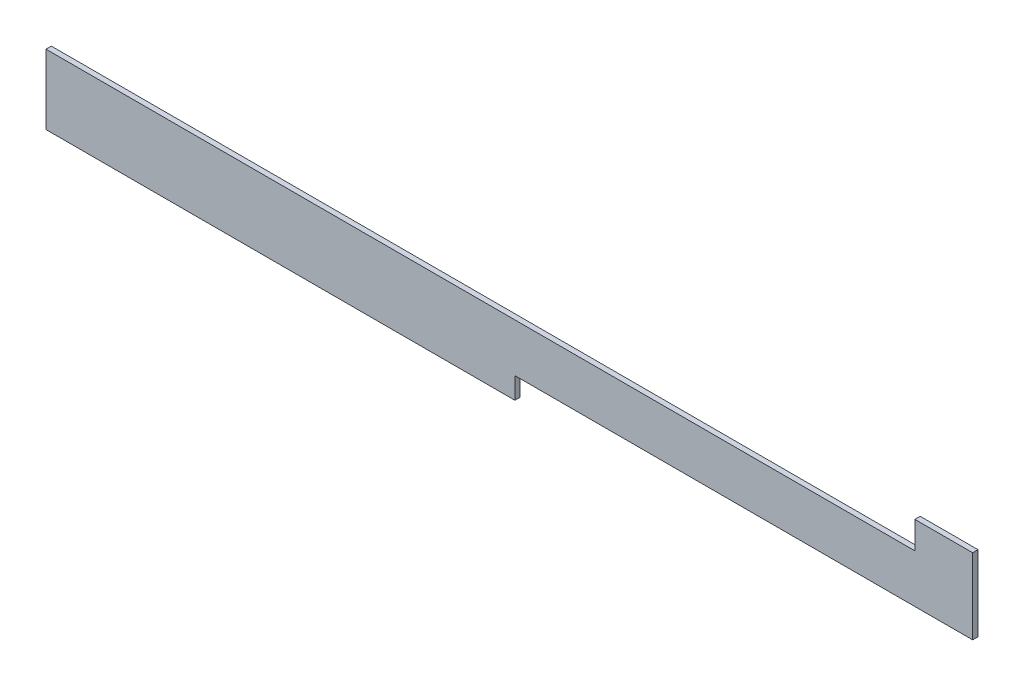
SolidWorks part; units mm, degrees
ref_plane "Front Plane" through (0, 0, 0) normal (0, 0, 1) x (1, 0, 0)
ref_plane "Top Plane" through (0, 0, 0) normal (0, 1, 0) x (1, 0, 0)
ref_plane "Right Plane" through (0, 0, 0) normal (1, 0, 0) x (0, 0, -1)
sketch "Sketch1" plane through (0, 0, 0) normal (0, 0, 1) x (1, 0, 0)
  line L0 (241.1095, 30.5435) -> (241.1095, 14.351)
  line L1 (275.5036, -14.351) -> (3.302, -14.351)
  line L2 (275.5036, -14.351) -> (275.5036, 14.351)
  line L3 (241.1095, 14.351) -> (-275.5036, 14.351)
  line L4 (-275.5036, -14.351) -> (-275.5036, 14.351)
  line L5 (275.5036, -14.351) -> (-275.5036, 14.351) construction
  line L6 (275.5036, 14.351) -> (-275.5036, -14.351) construction
  line L7 (275.5036, 14.351) -> (275.5036, 30.5435)
  line L8 (275.5036, 30.5435) -> (241.1095, 30.5435)
  line L9 (241.1095, -12.5594) -> (241.1095, -14.351)
  line L11 (3.302, -27.051) -> (-275.5036, -27.051)
  line L12 (-275.5036, -27.051) -> (-275.5036, -14.351)
  line L13 (3.302, -14.351) -> (3.302, -27.051)
  point P0 (0, 0)
  dimension "D1" = 28.702
  dimension "D2" = 551.0073
  dimension "D3" = 34.3941
  dimension "D4" = 44.8945
  dimension "D5" = 12.7
extrude "Boss-Extrude1" add sketch "Sketch1" along normal blind 3.175
